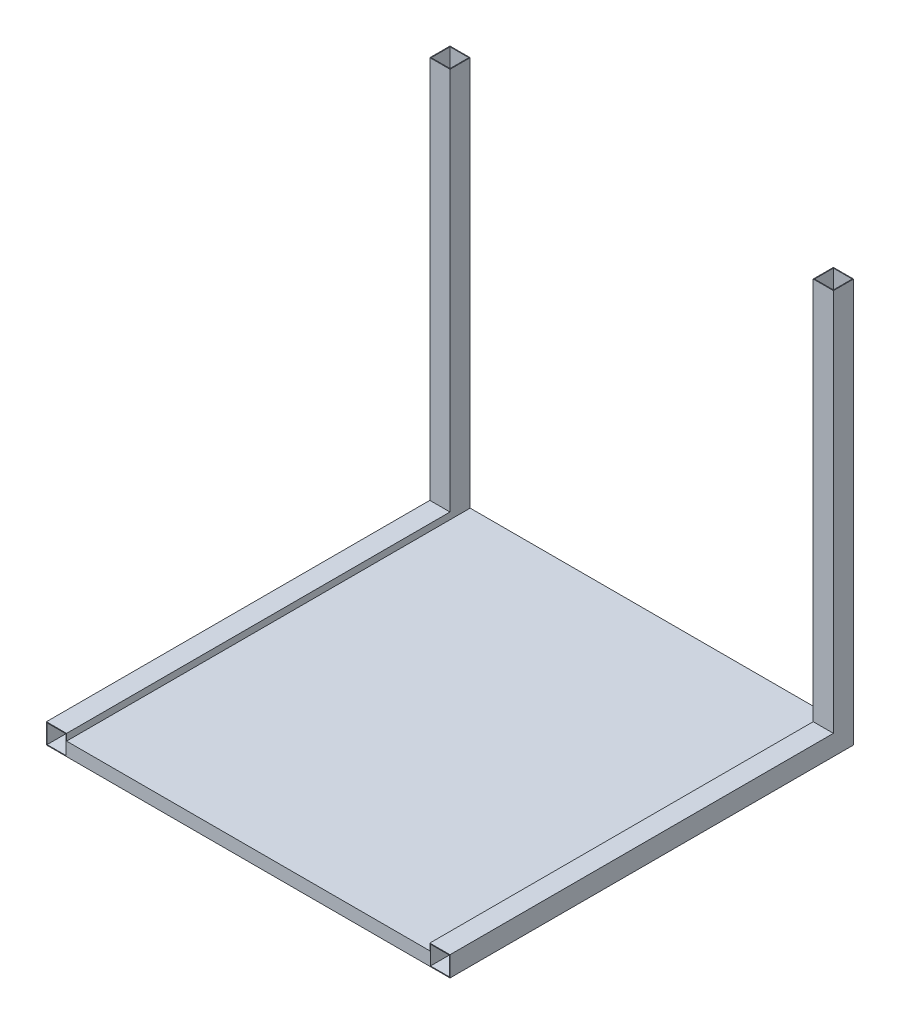
SolidWorks part; units mm, degrees
ref_plane "Front Plane" through (0, 0, 0) normal (0, 0, 1) x (1, 0, 0)
ref_plane "Top Plane" through (0, 0, 0) normal (0, 1, 0) x (1, 0, 0)
ref_plane "Right Plane" through (0, 0, 0) normal (1, 0, 0) x (0, 0, -1)
sketch "Sketch1" plane through (0, 0, 0) normal (0, 0, 1) x (1, 0, 0)
  line L1 (-300, 0) -> (-270, 0)
  line L2 (-300, 0) -> (-300, 30)
  line L3 (-300, 30) -> (-270, 30)
  line L4 (-270, 0) -> (-270, 30)
  line L5 (270, 0) -> (300, 0)
  line L6 (270, 0) -> (270, 30)
  line L7 (270, 30) -> (300, 30)
  line L8 (300, 0) -> (300, 30)
  dimension "D1" = 30
  dimension "D2" = 30
  dimension "D3" = 30
  dimension "D4" = 30
  dimension "D5" = 270
  dimension "D6" = 600
extrude "Extrude-Thin1" add sketch "Sketch1" against normal blind 570 thin thin type one direction reverse wall 1
sketch "Sketch3" plane through (0, 30, 0) normal (0, 1, 0) x (1, 0, 0)
  line L0 (300, 570) -> (270, 570) construction
  line L1 (-300, 600) -> (-270, 600)
  line L2 (-300, 600) -> (-300, 570)
  line L3 (-300, 570) -> (-270, 570)
  line L4 (-270, 600) -> (-270, 570)
  line L5 (270, 600) -> (300, 600)
  line L6 (270, 600) -> (270, 570)
  line L7 (270, 570) -> (300, 570)
  line L8 (300, 600) -> (300, 570)
  line L9 (-270, 570) -> (-300, 570) construction
  line L10 (-300, 570) -> (-300, 0) construction
  line L11 (-270, 570) -> (-270, 0) construction
  line L12 (300, 570) -> (300, 0) construction
  line L13 (270, 570) -> (270, 0) construction
  dimension "D1" = 30
  dimension "D2" = 30
  dimension "D3" = 30
extrude "Extrude-Thin2" add sketch "Sketch3" along normal blind 570 and the other way blind 30 separate body thin
sketch "Sketch4" plane through (-270, 0, 0) normal (1, 0, 0) x (0, 0, -1)
  line L0 (600, 0) -> (600, 600) construction
  line L1 (600, 600) -> (570, 600) construction
  line L3 (570, 0) -> (600, 0) construction
  line L5 (0, 0) -> (570, 0) construction
  line L8 (600, 0) -> (600, 20)
  line L9 (600, 600) -> (570, 600)
  line L11 (570, 0) -> (600, 0)
  line L12 (0, 20) -> (0, 0)
  line L13 (0, 0) -> (570, 0)
  line L15 (570, 20) -> (0, 20)
  line L16 (570, 20) -> (600, 20)
  dimension "D1" = 20
  dimension "D2" = 20
extrude "Boss-Extrude1" add sketch "Sketch4" along normal up to surface (540 mm away) contours L13 L11 L8 L16 L15 L12 up to face at (270, 15, -285)
surface "Surface-Fill1"
surface "Surface-Fill2"
sketch "Sketch5" plane through (0, 0, 0) normal (0, -1, 0) x (-1, 0, 0)
  line L0 (-300, 600) -> (-300, 0) construction
  line L1 (-250, 550) -> (-120, 550)
  line L2 (-250, 550) -> (-250, 450)
  line L3 (-250, 450) -> (-120, 450)
  line L4 (-120, 550) -> (-120, 450)
  line L5 (120, 550) -> (250, 550)
  line L6 (120, 550) -> (120, 450)
  line L7 (120, 450) -> (250, 450)
  line L8 (250, 550) -> (250, 450)
  line L9 (250, 50) -> (120, 50)
  line L10 (250, 50) -> (250, 150)
  line L11 (250, 150) -> (120, 150)
  line L12 (120, 50) -> (120, 150)
  line L13 (-250, 150) -> (-120, 150)
  line L14 (-250, 150) -> (-250, 50)
  line L15 (-250, 50) -> (-120, 50)
  line L16 (-120, 150) -> (-120, 50)
  line L17 (300, 0) -> (-300, 0) construction
  line L18 (-300, 600) -> (300, 600) construction
  line L19 (300, 600) -> (300, 0) construction
  dimension "D1" = 130
  dimension "D2" = 100
  dimension "D3" = 130
  dimension "D4" = 100
  dimension "D5" = 130
  dimension "D6" = 130
  dimension "D7" = 100
  dimension "D8" = 100
  dimension "D9" = 50
  dimension "D10" = 50
  dimension "D11" = 50
  dimension "D12" = 50
  dimension "D13" = 50
  dimension "D14" = 50
  dimension "D15" = 50
  dimension "D16" = 50
extrude "Boss-Extrude2" add sketch "Sketch5" along normal blind 10
